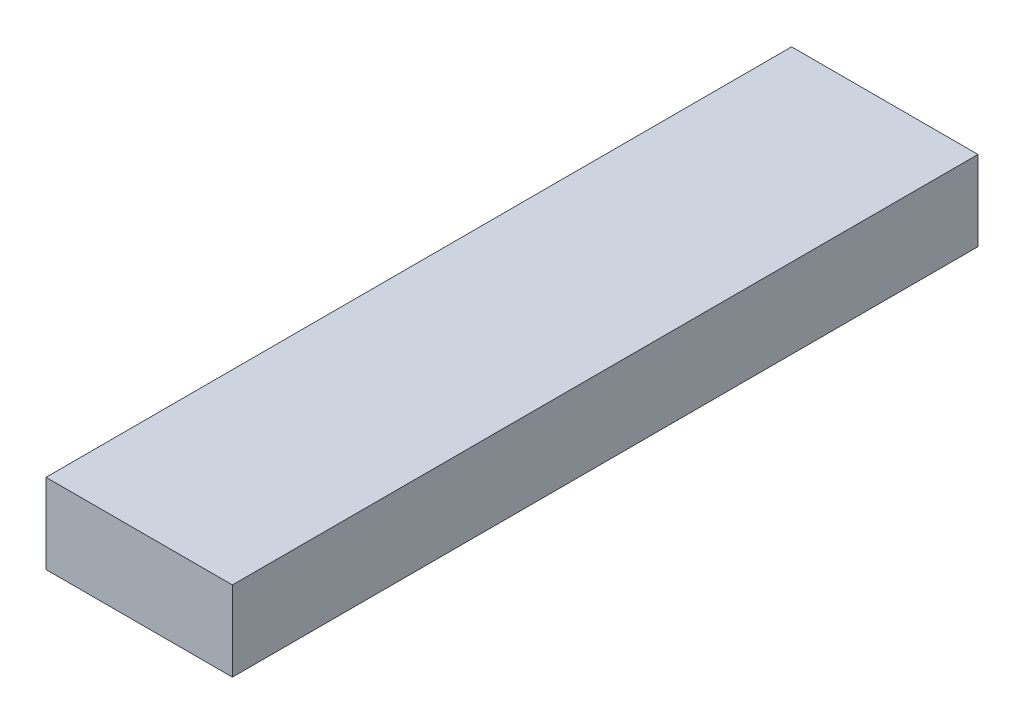
SolidWorks part; units mm, degrees
ref_plane "Front Plane" through (0, 0, 0) normal (0, 0, 1) x (1, 0, 0)
ref_plane "Top Plane" through (0, 0, 0) normal (0, 1, 0) x (1, 0, 0)
ref_plane "Right Plane" through (0, 0, 0) normal (1, 0, 0) x (0, 0, -1)
sketch "Sketch1" plane through (0, 0, 0) normal (0, 0, 1) x (1, 0, 0)
  line L1 (0, 0) -> (88.9, 0)
  line L2 (0, 0) -> (0, 38.1)
  line L3 (0, 38.1) -> (88.9, 38.1)
  line L4 (88.9, 0) -> (88.9, 38.1)
  dimension "D1" = 88.9
  dimension "D2" = 38.1
extrude "Boss-Extrude1" add sketch "Sketch1" along normal blind 355.6
